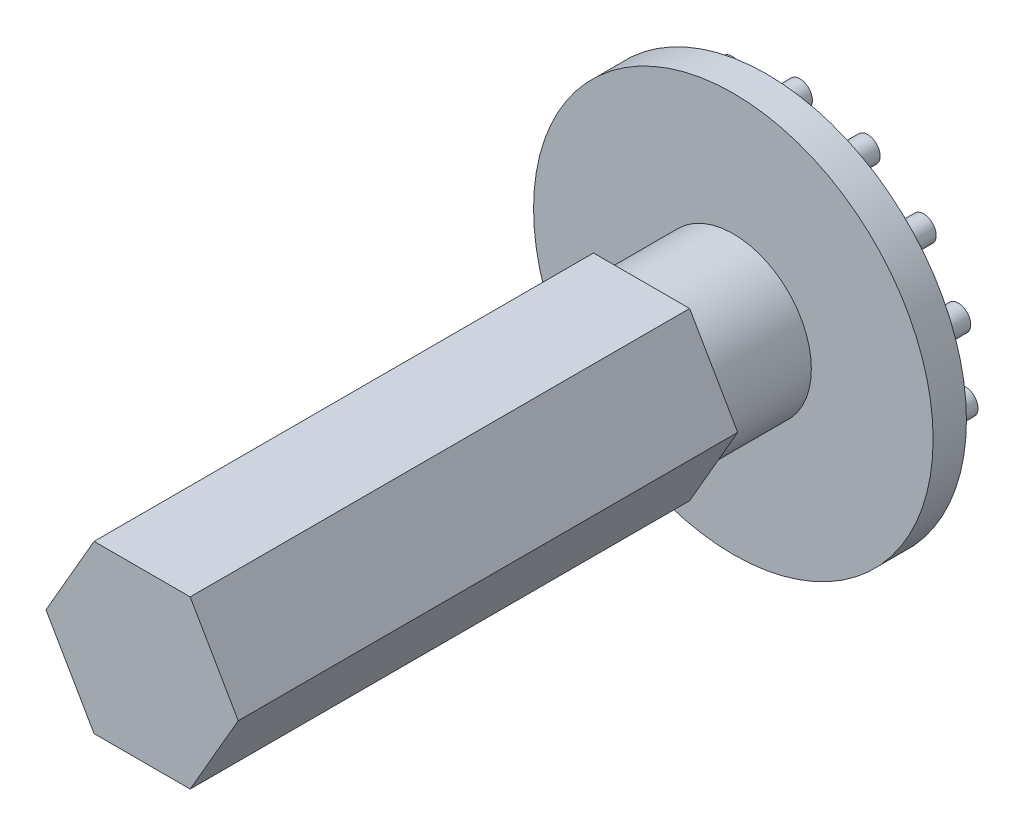
SolidWorks part; units mm, degrees
ref_plane "Front Plane" through (0, 0, 0) normal (0, 0, 1) x (1, 0, 0)
ref_plane "Top Plane" through (0, 0, 0) normal (0, 1, 0) x (1, 0, 0)
ref_plane "Right Plane" through (0, 0, 0) normal (1, 0, 0) x (0, 0, -1)
sketch "Sketch1" plane through (0, 0, 0) normal (0, 0, 1) x (1, 0, 0)
  circle A0 centre (0, 0) radius 4.55
  circle A1 centre (0, 0) radius 15.24
  dimension "D1" = 9.1
  dimension "D2" = 30.48
extrude "Boss-Extrude1" add sketch "Sketch1" along normal blind 2.54
sketch "Sketch2" plane through (0, 0, 2.54) normal (0, 0, 1) x (1, 0, 0)
  circle A0 centre (0, 0) radius 5.95
  dimension "D1" = 11.9
extrude "Boss-Extrude2" add sketch "Sketch2" along normal blind 7
sketch "Sketch3" plane through (0, 0, 9.54) normal (0, 0, 1) x (1, 0, 0)
  line L1 (3.6662, 6.35) -> (-3.6662, 6.35)
  line L2 (-3.6662, 6.35) -> (-7.3323, 0)
  line L3 (-7.3323, 0) -> (-3.6662, -6.35)
  line L4 (-3.6662, -6.35) -> (3.6662, -6.35)
  line L5 (3.6662, -6.35) -> (7.3323, 0)
  line L6 (7.3323, 0) -> (3.6662, 6.35)
  circle A1 centre (0, 0) radius 6.35 construction
  dimension "D1" = 12.7
extrude "Boss-Extrude3" add sketch "Sketch3" along normal blind 38.1
sketch "Sketch4" [suppressed] plane through (0, 0, 47.64) normal (0, 0, 1) x (1, 0, 0)
  line L1 (-0.635, 1.905) -> (0.635, 1.905)
  line L2 (-0.635, 1.905) -> (-0.635, 4.445)
  line L3 (-0.635, 4.445) -> (0.635, 4.445)
  line L4 (0.635, 1.905) -> (0.635, 4.445)
  point P4 (0, 1.905)
  dimension "D1" = 2.54
  dimension "D2" = 1.905
  dimension "D3" = 1.27
extrude "Boss-Extrude4" [suppressed] add sketch "Sketch4" against normal blind 2.54
sketch "Sketch5" plane through (0, 0, 0) normal (0, 0, -1) x (-1, 0, 0)
  line L0 (0, 0) -> (0, 12.7) construction
  circle A0 centre (0, 12.7) radius 0.9525
  circle A13 centre (5.1656, 11.602) radius 0.9525
  circle A14 centre (9.4379, 8.498) radius 0.9525
  circle A15 centre (12.0784, 3.9245) radius 0.9525
  circle A16 centre (12.6304, -1.3275) radius 0.9525
  circle A17 centre (10.9985, -6.35) radius 0.9525
  circle A18 centre (7.4649, -10.2745) radius 0.9525
  circle A19 centre (2.6405, -12.4225) radius 0.9525
  circle A20 centre (-2.6405, -12.4225) radius 0.9525
  circle A21 centre (-7.4649, -10.2745) radius 0.9525
  circle A22 centre (-10.9985, -6.35) radius 0.9525
  circle A23 centre (-12.6304, -1.3275) radius 0.9525
  circle A24 centre (-12.0784, 3.9245) radius 0.9525
  circle A25 centre (-9.4379, 8.498) radius 0.9525
  circle A26 centre (-5.1656, 11.602) radius 0.9525
  dimension "D2" = 1.905
  dimension "D1" = 12.7
  dimension "D3" = 15
  dimension "D4" = 12.7
extrude "Boss-Extrude5" add sketch "Sketch5" along normal blind 2.54
